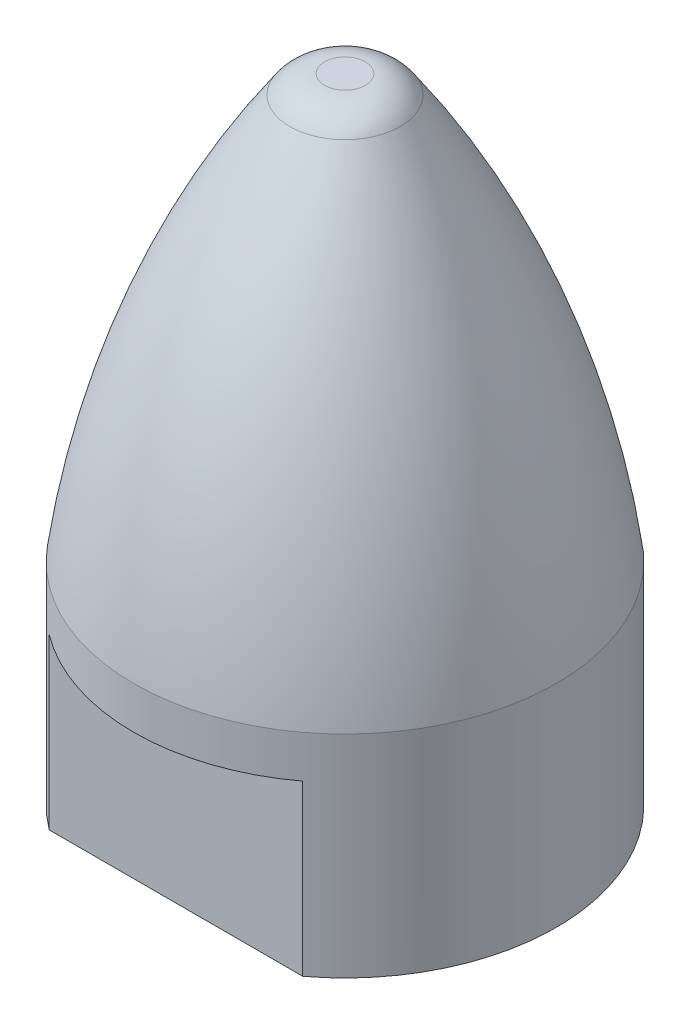
SolidWorks part; units mm, degrees
material "1060 Alloy"
ref_plane "Front Plane" through (0, 0, 0) normal (0, 0, 1) x (1, 0, 0)
ref_plane "Top Plane" through (0, 0, 0) normal (0, 1, 0) x (1, 0, 0)
ref_plane "Right Plane" through (0, 0, 0) normal (1, 0, 0) x (0, 0, -1)
sketch "Sketch1" plane through (0, 0, 0) normal (0, 0, 1) x (1, 0, 0)
  line L0 (0, 0) -> (0, 15) construction
  line L1 (0, 0) -> (-5, 0)
  line L2 (-5, 0) -> (-5, 5)
  line L3 (0, 15) -> (-1, 15)
  line L4 (0, 0) -> (0, 15) construction
  line L5 (0, 0) -> (0, 15)
  arc A0 (-1, 15) -> (-5, 5) centre (16.8051, 2.078) ccw
  dimension "D5" = 22
  dimension "D1" = 1
  dimension "D2" = 5
  dimension "D3" = 15
  dimension "D4" = 5
revolve "Revolve2" add sketch "Sketch1" angle 360 about L5
fillet "Fillet2" radius 1 1 edges at (0, 15, -1)
sketch "Sketch4" plane through (0, 0, 0) normal (1, 0, 0) x (0, 0, -1)
  line L0 (-5, 0) -> (5, 0) construction
  line L1 (-4, 0) -> (-7, 0)
  line L2 (-4, 0) -> (-4, 4)
  line L3 (-4, 4) -> (-7, 4)
  line L4 (-7, 0) -> (-7, 4)
  line L5 (0, 0) -> (0, 5) construction
  line L6 (5, 5) -> (-5, 5) construction
  line L7 (4, 4) -> (7, 4)
  line L8 (4, 0) -> (4, 4)
  line L9 (4, 0) -> (7, 0)
  line L10 (7, 0) -> (7, 4)
  dimension "D1" = 4
  dimension "D2" = 3
  dimension "D3" = 4
extrude "Cut-Extrude1" cut sketch "Sketch4" against normal through all both and the other way through all
hole_wizard "M5x0.8 Tapped Hole1" positions "Sketch5" profile "Sketch7" tap size "M5x0.8" standard "JIS"
sketch "Sketch5" plane through (0, 0, 0) normal (0, -1, 0) x (-1, 0, 0)
  point P0 (0, 0)
sketch "Sketch7" plane through (0, 0, 0) normal (1, 0, 0) x (0, 0, -1)
  line L0 (0, 0) -> (0, 9.2618)
  line L1 (0, 9.2618) -> (2.1, 8)
  line L2 (2.1, 8) -> (2.1, 0)
  line L5 (2.1, 0) -> (0, 0)
  line L10 (0, 9.2618) -> (-2.1, 8) construction
  line L11 (0, -6.35) -> (0, 107.95) construction
  dimension "Tap Drill Dia." = 4.2
  dimension "Tap Drill Depth" = 8
  dimension "Drill Angle" = 118
cosmetic thread "Hole Thread1" parameters "D1"=6, "D2"=5
